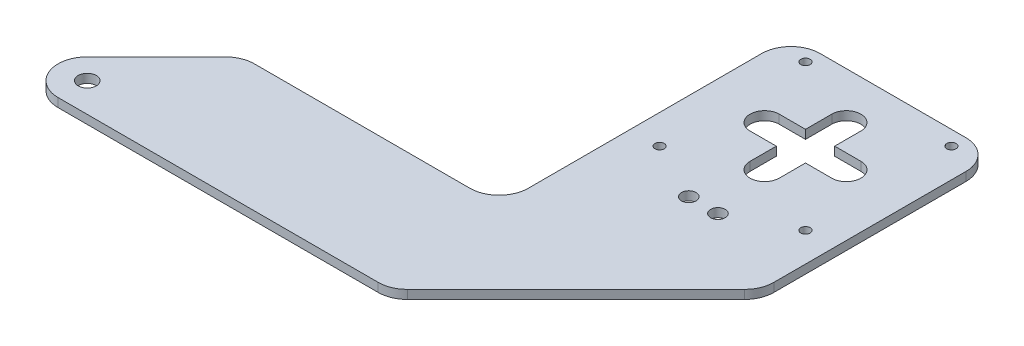
SolidWorks part; units mm, degrees
material "Thornel Mat VMA"
ref_plane "前视基准面" through (0, 0, 0) normal (0, 0, 1) x (1, 0, 0)
ref_plane "上视基准面" through (0, 0, 0) normal (0, 1, 0) x (1, 0, 0)
ref_plane "右视基准面" through (0, 0, 0) normal (1, 0, 0) x (0, 0, -1)
sketch "草图1" plane through (0, 0, 0) normal (0, 1, 0) x (1, 0, 0)
  line L1 (0, 0) -> (50, 0) construction
  line L2 (0, 0) -> (0, 50) construction
  line L3 (0, 50) -> (50, 50) construction
  line L4 (50, 0) -> (50, 50) construction
  line L5 (25, 50) -> (25, 0) construction
  line L6 (0, 25) -> (50, 25) construction
  line L7 (-10, -5) -> (60, -5)
  line L8 (-10, -5) -> (-10, 55)
  line L9 (-10, 55) -> (60, 55)
  line L10 (60, -5) -> (60, 55)
  line L11 (-10, -5) -> (60, 55) construction
  line L12 (-10, 55) -> (60, -5) construction
  circle A0 centre (0, 50) radius 1.6
  circle A1 centre (50, 50) radius 1.6
  circle A2 centre (50, 0) radius 1.6
  circle A3 centre (0, 0) radius 1.6
  point P8 (25, 25)
  point P568 (25, 25)
  dimension "D3" = 3.2
  dimension "D1" = 50
  dimension "D2" = 50
  dimension "D4" = 10
  dimension "D5" = 60
extrude "凸台-拉伸1" add sketch "草图1" along normal blind 3
sketch "草图2" plane through (0, 0, 0) normal (0, 1, 0) x (1, 0, 0)
  line L0 (60, -5) -> (60, 55) construction
  line L1 (-10, -5) -> (60, -5)
  line L2 (-10, -5) -> (-10, -45)
  line L3 (-10, -45) -> (60, -45) construction
  line L4 (60, -5) -> (60, -25)
  line L5 (25, -45) -> (25, -5) construction
  line L6 (-10, -25) -> (60, -25) construction
  line L8 (60, -25) -> (-3.6396, -88.6396)
  line L9 (-58.1724, -88.6396) -> (-3.6396, -88.6396)
  line L10 (-10, -45) -> (-98, -45)
  line L12 (-141.6396, -88.6396) -> (-58.1724, -88.6396)
  line L15 (-141.6396, -88.6396) -> (-98, -45)
  point P912 (25, -25)
  dimension "D1" = 20
  dimension "D2" = 90
  dimension "D3" = 45
  dimension "D4" = 135
  dimension "D6" = 138
extrude "凸台-拉伸2" add sketch "草图2" along normal blind 3
fillet "圆角1" radius 10 5 edges at (-10, 1.5, 45) (-3.6396, 1.5, 88.6396) (-10, 1.5, -55) (60, 1.5, -55) (60, 1.5, 25)
fillet "圆角3" radius 10 2 edges at (-141.6396, 1.5, 88.6396) (-98, 1.5, 45)
sketch "草图4" plane through (0, 3, 0) normal (0, 1, 0) x (1, 0, 0)
  line L4 (-117.4975, -88.6396) -> (-7.7817, -88.6396) construction
  arc A0 (-124.5685, -71.5685) -> (-117.4975, -88.6396) centre (-117.4975, -78.6396) ccw construction
  circle A1 centre (-117.4975, -78.6396) radius 3.1
  dimension "D1" = 6.2
  dimension "D2" = 6.9
  dimension "D3" = 10
extrude "切除-拉伸1" cut sketch "草图4" against normal blind 10
sketch "草图5" plane through (0, 3, 0) normal (0, 1, 0) x (1, 0, 0)
  line L0 (0, 50) -> (50, 50) construction
  line L1 (50, 0) -> (50, 50) construction
  line L2 (0, 0) -> (50, 0) construction
  line L3 (0, 50) -> (0, 0) construction
  line L4 (0, 25) -> (50, 25) construction
  line L5 (11, 25) -> (39, 25) construction
  line L6 (11, 30) -> (20, 30)
  line L7 (11, 20) -> (20, 20)
  line L8 (0, 50) -> (50, 0) construction
  line L9 (25, 39) -> (25, 11) construction
  line L10 (20, 39) -> (20, 30)
  line L11 (0, -10) -> (50, -10) construction
  line L12 (25, 0) -> (25, -10) construction
  line L13 (30, 39) -> (30, 30)
  line L14 (30, 30) -> (39, 30)
  line L15 (30, 20) -> (39, 20)
  line L16 (20, 20) -> (20, 11)
  line L17 (30, 20) -> (30, 11)
  circle A0 centre (20, -10) radius 2.5
  circle A1 centre (30, -10) radius 2.5
  arc A2 (11, 30) -> (11, 20) centre (11, 25) ccw
  arc A3 (39, 20) -> (39, 30) centre (39, 25) ccw
  arc A4 (20, 39) -> (30, 39) centre (25, 39) cw
  arc A5 (30, 11) -> (20, 11) centre (25, 11) cw
  point P13 (25, 25)
  point P20 (25, 25)
  dimension "D6" = 5
  dimension "D1" = 5
  dimension "D2" = 28
  dimension "D5" = 10
extrude "切除-拉伸2" cut sketch "草图5" against normal through all
